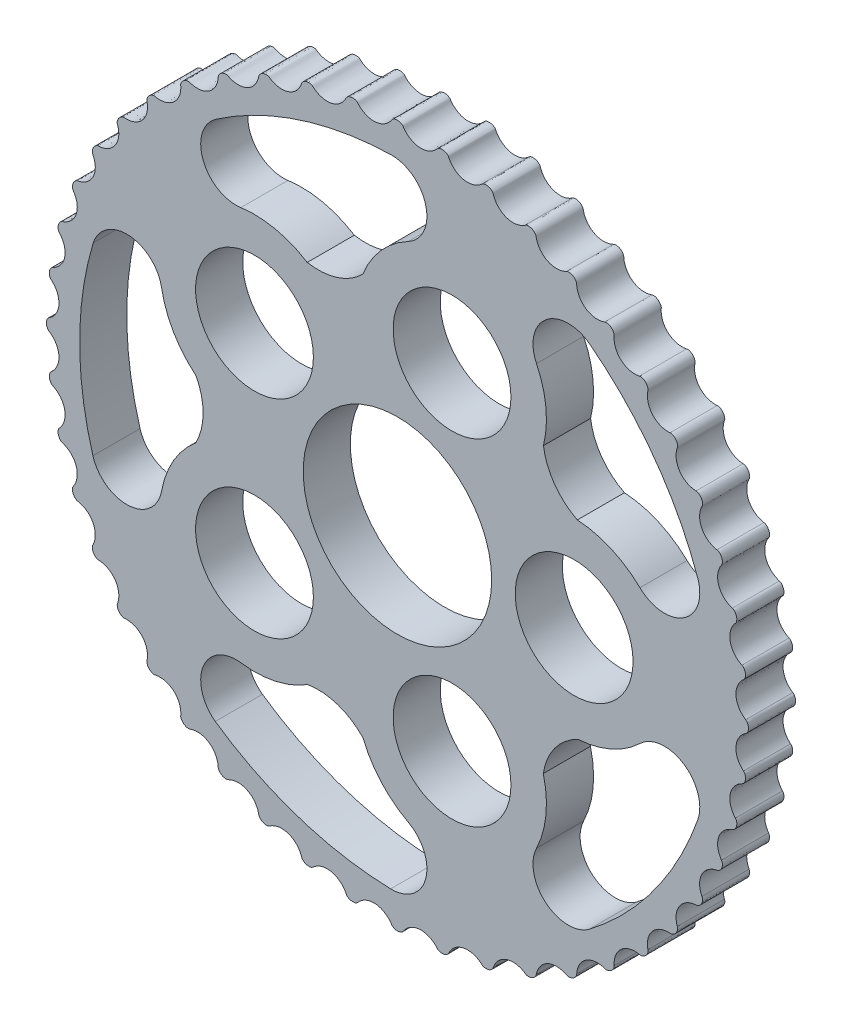
SolidWorks part; units mm, degrees
ref_plane "前视基准面" through (0, 0, 0) normal (0, 0, 1) x (1, 0, 0)
ref_plane "上视基准面" through (0, 0, 0) normal (0, 1, 0) x (1, 0, 0)
ref_plane "右视基准面" through (0, 0, 0) normal (1, 0, 0) x (0, 0, -1)
other "图形1"
other "图形 (闭合) -1"
sketch "草图1" plane through (0, 0, 0) normal (0, 0, 1) x (1, 0, 0)
  circle A14 centre (0, 0) radius 8
  circle A15 centre (-12.1353, 8.8168) radius 5
  circle A16 centre (4.6353, 14.2658) radius 5
  circle A17 centre (15, 0) radius 5
  circle A18 centre (4.6353, -14.2658) radius 5
  circle A19 centre (-12.1353, -8.8168) radius 5
  arc A22 (-15.3994, 22.1779) -> (-0.4976, 26.9948) centre (0.1503, -0.4678) cw
  arc A23 (-15.3994, 22.1779) -> (-13.2927, 16.7327) centre (-13.7012, 19.7047) ccw
  arc A24 (-0.4976, 26.9948) -> (0.9158, 21.3487) centre (-0.4976, 23.9948) cw
  arc A25 (-13.2927, 16.7327) -> (-7.6572, 15.521) centre (-12.143, 8.369) cw
  arc A26 (0.9158, 21.3487) -> (-2.9414, 17.0153) centre (4.8704, 13.9452) ccw
  arc A27 (-7.6572, 15.521) -> (-2.9414, 17.0153) centre (-6.7149, 20.7352) ccw
  arc A28 (12.3951, 12.0786) -> (15.2736, 8.0555) centre (17.6454, 12.7938) ccw
  arc A29 (20.5868, 5.7261) -> (15.2736, 8.0555) centre (14.7677, -0.3227) ccw
  arc A30 (11.8061, 17.8128) -> (12.3951, 12.0786) centre (4.207, 14.1348) cw
  arc A31 (16.3337, 21.499) -> (11.8061, 17.8128) centre (14.5064, 19.1197) ccw
  arc A32 (16.3337, 21.499) -> (25.5198, 8.8152) centre (-0.3985, -0.2875) cw
  arc A33 (25.5198, 8.8152) -> (20.5868, 5.7261) centre (22.6667, 7.8881) cw
  arc A34 (15.3178, -8.0559) -> (12.381, -12.0367) centre (17.6203, -12.8283) ccw
  arc A35 (11.8075, -17.8097) -> (12.381, -12.0367) centre (4.2565, -14.1446) ccw
  arc A36 (20.5892, -5.7238) -> (15.3178, -8.0559) centre (14.743, 0.3668) cw
  arc A37 (25.4942, -8.8907) -> (20.5892, -5.7238) centre (22.6667, -7.8881) ccw
  arc A38 (25.4942, -8.8907) -> (16.2698, -21.5468) centre (-0.3966, 0.2902) cw
  arc A39 (16.2698, -21.5468) -> (11.8075, -17.8097) centre (14.5064, -19.1197) cw
  arc A40 (-2.9282, -17.0575) -> (-7.6217, -15.4946) centre (-6.7554, -20.7221) ccw
  arc A41 (-13.2893, -16.7332) -> (-7.6217, -15.4946) centre (-12.137, -8.4192) ccw
  arc A42 (0.9188, -21.3503) -> (-2.9282, -17.0575) centre (4.9047, -13.9081) cw
  arc A43 (-0.5775, -26.9938) -> (0.9188, -21.3503) centre (-0.4977, -23.9948) ccw
  arc A44 (-0.5775, -26.9938) -> (-15.4646, -22.1318) centre (0.1534, 0.4668) cw
  arc A45 (-15.4646, -22.1318) -> (-13.2893, -16.7332) centre (-13.7012, -19.7047) cw
  arc A46 (-17.1275, -2.4862) -> (-17.0915, 2.4605) centre (-21.7954, 0.0213) ccw
  arc A47 (-20.0208, 7.4681) -> (-17.0915, 2.4605) centre (-11.7576, 8.9413) ccw
  arc A48 (-20.0214, -7.4714) -> (-17.1275, -2.4862) centre (-11.7117, -8.9625) cw
  arc A49 (-25.8511, -7.7923) -> (-20.0214, -7.4714) centre (-22.9742, -6.9415) ccw
  arc A50 (-25.8511, -7.7923) -> (-25.8274, 7.8686) centre (0.4914, -0.0017) cw
  arc A51 (-25.8274, 7.8686) -> (-20.0208, 7.4681) centre (-22.9742, 6.9415) cw
  spline S0 degree 3 poles (-23.7568, 17.5894) (-23.7638, 17.6206) (-23.7873, 17.6724) (-23.7946, 17.7527) (-23.7831, 17.8328) (-23.7576, 17.926) (-23.7125, 18.0342) (-23.6398, 18.1534) (-23.536, 18.2576) (-23.4214, 18.3351) (-23.3276, 18.3772) (-23.2577, 18.3994) (-23.1885, 18.3963) (-23.122, 18.3956) (-23.0375, 18.3863) (-22.9358, 18.3866) (-22.7821, 18.3963) (-22.5426, 18.4408) (-22.2285, 18.5461) (-21.9362, 18.7184) (-21.7337, 18.8947) (-21.622, 19.0229) (-21.5377, 19.1337) (-21.4287, 19.302) (-21.3257, 19.519) (-21.2567, 19.7619) (-21.228, 19.9486) (-21.2184, 20.1013) (-21.2209, 20.2334) (-21.2306, 20.3759) (-21.245, 20.478) (-21.2577, 20.5398) knots 0 0 0 0 0.021407 0.037439 0.053081 0.075244 0.101831 0.131128 0.167942 0.199083 0.222894 0.236703 0.24736 0.268789 0.281242 0.304031 0.336576 0.384054 0.466277 0.556571 0.608579 0.644913 0.669953 0.701577 0.778695 0.829212 0.869703 0.904632 0.931224 0.957906 1 1 1 1
  spline S1 degree 3 poles (-21.2577, 20.5398) (-21.2606, 20.5717) (-21.2771, 20.626) (-21.2739, 20.7066) (-21.252, 20.7845) (-21.2145, 20.8736) (-21.1557, 20.975) (-21.0681, 21.0837) (-20.9516, 21.1735) (-20.8279, 21.2353) (-20.7293, 21.2649) (-20.6571, 21.2777) (-20.5889, 21.2657) (-20.5231, 21.2562) (-20.4405, 21.236) (-20.3397, 21.223) (-20.1859, 21.2126) (-19.9427, 21.2254) (-19.6176, 21.2888) (-19.3053, 21.4215) (-19.0816, 21.5698) (-18.954, 21.6823) (-18.8559, 21.7813) (-18.7259, 21.9339) (-18.5955, 22.1356) (-18.4954, 22.3674) (-18.4426, 22.5488) (-18.4132, 22.6988) (-18.3984, 22.8302) (-18.3893, 22.9727) (-18.3903, 23.0758) (-18.3949, 23.1387) knots 0 0 0 0 0.021407 0.037439 0.05308 0.075244 0.101831 0.131128 0.167942 0.199083 0.222894 0.236703 0.24736 0.268789 0.281242 0.304031 0.336576 0.384054 0.466277 0.556571 0.608579 0.644913 0.669953 0.701577 0.778695 0.829212 0.869703 0.904632 0.931224 0.957906 1 1 1 1
  spline S2 degree 3 poles (-18.3949, 23.1387) (-18.3935, 23.1707) (-18.4028, 23.2268) (-18.3891, 23.3063) (-18.3572, 23.3806) (-18.3085, 23.4641) (-18.2369, 23.5569) (-18.1358, 23.6533) (-18.0086, 23.7271) (-17.8779, 23.7722) (-17.7763, 23.7887) (-17.7031, 23.792) (-17.6371, 23.7711) (-17.573, 23.7532) (-17.4938, 23.7224) (-17.3955, 23.6963) (-17.2445, 23.6659) (-17.0016, 23.6469) (-16.671, 23.6673) (-16.3441, 23.7581) (-16.1029, 23.8759) (-15.9618, 23.9709) (-15.8516, 24.0561) (-15.7028, 24.1905) (-15.5471, 24.3734) (-15.4177, 24.5902) (-15.3416, 24.7631) (-15.2929, 24.9081) (-15.261, 25.0363) (-15.2335, 25.1765) (-15.221, 25.2788) (-15.2173, 25.3418) knots 0 0 0 0 0.021407 0.037439 0.05308 0.075244 0.101831 0.131128 0.167942 0.199083 0.222894 0.236703 0.24736 0.268789 0.281242 0.304031 0.336576 0.384054 0.466277 0.556571 0.608579 0.644913 0.669953 0.701577 0.778695 0.829212 0.869703 0.904632 0.931224 0.957906 1 1 1 1
  spline S3 degree 3 poles (-15.2173, 25.3418) (-15.2118, 25.3733) (-15.2137, 25.4302) (-15.1897, 25.5071) (-15.1484, 25.5767) (-15.0892, 25.6531) (-15.0061, 25.7358) (-14.8933, 25.8181) (-14.7575, 25.8747) (-14.6221, 25.9024) (-14.5192, 25.9054) (-14.4462, 25.8992) (-14.3834, 25.8699) (-14.3222, 25.8437) (-14.2477, 25.8028) (-14.1537, 25.7642) (-14.0079, 25.7143) (-13.7696, 25.6638) (-13.4392, 25.6408) (-13.1032, 25.6882) (-12.8487, 25.7735) (-12.6964, 25.8492) (-12.576, 25.9194) (-12.4109, 26.0331) (-12.2327, 26.1942) (-12.0761, 26.3922) (-11.9781, 26.5537) (-11.9109, 26.6911) (-11.8626, 26.8141) (-11.817, 26.9495) (-11.7912, 27.0493) (-11.7793, 27.1113) knots 0 0 0 0 0.021407 0.037439 0.05308 0.075244 0.101831 0.131128 0.167942 0.199083 0.222894 0.236703 0.24736 0.268789 0.281242 0.304031 0.336576 0.384054 0.466277 0.556571 0.608579 0.644913 0.669953 0.701577 0.778695 0.829212 0.869703 0.904632 0.931224 0.957906 1 1 1 1
  spline S4 degree 3 poles (-11.7793, 27.1113) (-11.7698, 27.1418) (-11.7642, 27.1984) (-11.7304, 27.2716) (-11.6804, 27.3352) (-11.6117, 27.4032) (-11.5185, 27.4743) (-11.3959, 27.5412) (-11.254, 27.5795) (-11.116, 27.5894) (-11.0137, 27.579) (-10.9421, 27.5632) (-10.8837, 27.526) (-10.8264, 27.492) (-10.7579, 27.4418) (-10.6697, 27.3912) (-10.5317, 27.3227) (-10.3021, 27.2415) (-9.9774, 27.1756) (-9.6381, 27.1787) (-9.3746, 27.2301) (-9.2138, 27.2853) (-9.0853, 27.3391) (-8.9068, 27.4304) (-8.7091, 27.5668) (-8.5279, 27.7427) (-8.4097, 27.89) (-8.3251, 28.0174) (-8.2612, 28.1331) (-8.1983, 28.2613) (-8.1597, 28.357) (-8.1398, 28.4168) knots 0 0 0 0 0.021407 0.037439 0.05308 0.075244 0.101831 0.131128 0.167942 0.199083 0.222894 0.236703 0.24736 0.268789 0.281242 0.304031 0.336576 0.384054 0.466277 0.556571 0.608579 0.644913 0.669953 0.701577 0.778695 0.829212 0.869703 0.904632 0.931224 0.957906 1 1 1 1
  spline S5 degree 3 poles (-8.1398, 28.4168) (-8.1264, 28.4459) (-8.1135, 28.5012) (-8.0704, 28.5694) (-8.0125, 28.6259) (-7.9355, 28.6844) (-7.8339, 28.7427) (-7.7036, 28.7931) (-7.5578, 28.8125) (-7.4198, 28.8043) (-7.3197, 28.7806) (-7.2507, 28.7556) (-7.1977, 28.7111) (-7.1454, 28.67) (-7.084, 28.6112) (-7.0032, 28.5495) (-6.8752, 28.4636) (-6.6582, 28.3531) (-6.3449, 28.2455) (-6.0081, 28.2042) (-5.7402, 28.2208) (-5.5735, 28.2545) (-5.4391, 28.2911) (-5.2502, 28.3583) (-5.0364, 28.4677) (-4.8338, 28.6184) (-4.6974, 28.7491) (-4.5969, 28.8644) (-4.5184, 28.9707) (-4.4393, 29.0897) (-4.3885, 29.1794) (-4.3611, 29.2362) knots 0 0 0 0 0.021407 0.037439 0.05308 0.075244 0.101831 0.131128 0.167942 0.199083 0.222894 0.236703 0.24736 0.268789 0.281242 0.304031 0.336576 0.384054 0.466277 0.556571 0.608579 0.644913 0.669953 0.701577 0.778695 0.829212 0.869703 0.904632 0.931224 0.957906 1 1 1 1
  spline S6 degree 3 poles (-4.3611, 29.2362) (-4.3439, 29.2632) (-4.3239, 29.3164) (-4.2723, 29.3784) (-4.2075, 29.4268) (-4.1236, 29.4748) (-4.0152, 29.5193) (-3.8794, 29.5523) (-3.7324, 29.5525) (-3.5966, 29.5263) (-3.5004, 29.4898) (-3.4353, 29.456) (-3.3886, 29.4049) (-3.3421, 29.3573) (-3.2889, 29.2911) (-3.2168, 29.2194) (-3.1012, 29.1175) (-2.9004, 28.9796) (-2.6038, 28.832) (-2.2753, 28.7471) (-2.0075, 28.7286) (-1.8379, 28.7402) (-1.6998, 28.759) (-1.5038, 28.8009) (-1.2775, 28.8815) (-1.057, 29.0045) (-0.9047, 29.1163) (-0.79, 29.2174) (-0.6983, 29.3126) (-0.6043, 29.4202) (-0.5423, 29.5026) (-0.5077, 29.5553) knots 0 0 0 0 0.021407 0.037439 0.05308 0.075244 0.101831 0.131128 0.167942 0.199083 0.222894 0.236703 0.24736 0.268789 0.281242 0.304031 0.336576 0.384054 0.466277 0.556571 0.608579 0.644913 0.669953 0.701577 0.778695 0.829212 0.869703 0.904632 0.931224 0.957906 1 1 1 1
  spline S7 degree 3 poles (-0.5077, 29.5553) (-0.4871, 29.5799) (-0.4604, 29.63) (-0.4011, 29.6847) (-0.3305, 29.7243) (-0.2411, 29.7608) (-0.1278, 29.7909) (0.0111, 29.8058) (0.1569, 29.7869) (0.2881, 29.7432) (0.3787, 29.6944) (0.4388, 29.6524) (0.4785, 29.5957) (0.5184, 29.5424) (0.5625, 29.4698) (0.6246, 29.3893) (0.726, 29.2732) (0.907, 29.1103) (1.1818, 28.9252) (1.4964, 28.7982) (1.7595, 28.7449) (1.9292, 28.7343) (2.0685, 28.7349) (2.2684, 28.7508) (2.5032, 28.8012) (2.7379, 28.8944) (2.9035, 28.9853) (3.0304, 29.0706) (3.1338, 29.153) (3.2409, 29.2474) (3.3132, 29.321) (3.3544, 29.3687) knots 0 0 0 0 0.021407 0.037439 0.05308 0.075244 0.101831 0.131128 0.167942 0.199083 0.222894 0.236703 0.24736 0.268789 0.281242 0.304031 0.336576 0.384054 0.466277 0.556571 0.608579 0.644913 0.669953 0.701577 0.778695 0.829212 0.869703 0.904632 0.931224 0.957906 1 1 1 1
  spline S8 degree 3 poles (3.3544, 29.3687) (3.378, 29.3904) (3.4111, 29.4366) (3.477, 29.4831) (3.5521, 29.5131) (3.6456, 29.5377) (3.7618, 29.5527) (3.9014, 29.5494) (4.0435, 29.5116) (4.1679, 29.4511) (4.2514, 29.3909) (4.3055, 29.3415) (4.3374, 29.28) (4.37, 29.222) (4.4043, 29.1442) (4.4553, 29.0563) (4.5407, 28.928) (4.6989, 28.7429) (4.9471, 28.5235) (5.2425, 28.3565) (5.4964, 28.2693) (5.6633, 28.2366) (5.8015, 28.219) (6.0017, 28.2088) (6.2411, 28.2281) (6.4859, 28.2898) (6.662, 28.3583) (6.799, 28.4263) (6.9122, 28.4945) (7.0308, 28.5742) (7.112, 28.6377) (7.1591, 28.6796) knots 0 0 0 0 0.021407 0.037439 0.05308 0.075244 0.101831 0.131128 0.167942 0.199083 0.222894 0.236703 0.24736 0.268789 0.281242 0.304031 0.336576 0.384054 0.466277 0.556571 0.608579 0.644913 0.669953 0.701577 0.778695 0.829212 0.869703 0.904632 0.931224 0.957906 1 1 1 1
  spline S9 degree 3 poles (7.1591, 28.6796) (7.1853, 28.698) (7.2241, 28.7395) (7.2955, 28.777) (7.3739, 28.797) (7.4698, 28.8092) (7.587, 28.8088) (7.725, 28.7873) (7.861, 28.7313) (7.9764, 28.6551) (8.0513, 28.5845) (8.0985, 28.5285) (8.1221, 28.4634) (8.1469, 28.4016) (8.1707, 28.32) (8.2098, 28.2262) (8.2777, 28.0878) (8.4104, 27.8836) (8.6279, 27.6337) (8.8989, 27.4296) (9.1392, 27.31) (9.3004, 27.2558) (9.4352, 27.2204) (9.6323, 27.1841) (9.8722, 27.1719) (10.123, 27.2012) (10.3065, 27.2461) (10.4512, 27.2957) (10.5723, 27.3485) (10.7003, 27.412) (10.7891, 27.4644) (10.8413, 27.4998) knots 0 0 0 0 0.021407 0.037439 0.05308 0.075244 0.101831 0.131128 0.167942 0.199083 0.222894 0.236703 0.24736 0.268789 0.281242 0.304031 0.336576 0.384054 0.466277 0.556571 0.608579 0.644913 0.669953 0.701577 0.778695 0.829212 0.869703 0.904632 0.931224 0.957906 1 1 1 1
  spline S10 degree 3 poles (10.8413, 27.4998) (10.8697, 27.5146) (10.9136, 27.5507) (10.9893, 27.5786) (11.0696, 27.5881) (11.1663, 27.5877) (11.2824, 27.5721) (11.4164, 27.5327) (11.5439, 27.4594) (11.6484, 27.3688) (11.7134, 27.2891) (11.7529, 27.2273) (11.7679, 27.1597) (11.7843, 27.0952) (11.7973, 27.0113) (11.8239, 26.9131) (11.8731, 26.7671) (11.978, 26.5473) (12.161, 26.2712) (12.4031, 26.0334) (12.6257, 25.8835) (12.7785, 25.8087) (12.9074, 25.756) (13.0982, 25.6942) (13.3344, 25.6509) (13.5869, 25.6472) (13.7747, 25.6678) (13.9246, 25.698) (14.0516, 25.7346) (14.1867, 25.7808) (14.2816, 25.8212) (14.338, 25.8495) knots 0 0 0 0 0.021407 0.037439 0.05308 0.075244 0.101831 0.131128 0.167942 0.199083 0.222894 0.236703 0.24736 0.268789 0.281242 0.304031 0.336576 0.384054 0.466277 0.556571 0.608579 0.644913 0.669953 0.701577 0.778695 0.829212 0.869703 0.904632 0.931224 0.957906 1 1 1 1
  spline S11 degree 3 poles (14.338, 25.8495) (14.3681, 25.8605) (14.4163, 25.8905) (14.495, 25.9082) (14.5759, 25.9072) (14.6717, 25.8942) (14.7848, 25.8635) (14.9125, 25.8071) (15.0293, 25.7177) (15.1211, 25.6143) (15.1752, 25.5267) (15.2063, 25.4603) (15.2122, 25.3913) (15.2202, 25.3253) (15.222, 25.2403) (15.2356, 25.1396) (15.2653, 24.9884) (15.3406, 24.7567) (15.486, 24.4591) (15.695, 24.1918) (15.8962, 24.0141) (16.0379, 23.92) (16.1588, 23.8508) (16.3399, 23.7648) (16.5685, 23.691) (16.8183, 23.6543) (17.0071, 23.6502) (17.1597, 23.6607) (17.2904, 23.6803) (17.4305, 23.7085) (17.5298, 23.7361) (17.5894, 23.7568) knots 0 0 0 0 0.021407 0.037439 0.05308 0.075244 0.101831 0.131128 0.167942 0.199083 0.222894 0.236703 0.24736 0.268789 0.281242 0.304031 0.336576 0.384054 0.466277 0.556571 0.608579 0.644913 0.669953 0.701577 0.778695 0.829212 0.869703 0.904632 0.931224 0.957906 1 1 1 1
  spline S12 degree 3 poles (17.5894, 23.7568) (17.6206, 23.7638) (17.6724, 23.7873) (17.7527, 23.7946) (17.8328, 23.7831) (17.926, 23.7576) (18.0342, 23.7125) (18.1534, 23.6398) (18.2576, 23.536) (18.3351, 23.4214) (18.3772, 23.3276) (18.3994, 23.2577) (18.3963, 23.1885) (18.3956, 23.122) (18.3863, 23.0375) (18.3866, 22.9358) (18.3963, 22.7821) (18.4408, 22.5426) (18.5461, 22.2285) (18.7184, 21.9362) (18.8947, 21.7337) (19.0229, 21.622) (19.1337, 21.5377) (19.302, 21.4287) (19.519, 21.3257) (19.7619, 21.2567) (19.9486, 21.228) (20.1013, 21.2184) (20.2334, 21.2209) (20.3759, 21.2306) (20.478, 21.245) (20.5398, 21.2577) knots 0 0 0 0 0.021407 0.037439 0.05308 0.075244 0.101831 0.131128 0.167942 0.199083 0.222894 0.236703 0.24736 0.268789 0.281242 0.304031 0.336576 0.384054 0.466277 0.556571 0.608579 0.644913 0.669953 0.701577 0.778695 0.829212 0.869703 0.904632 0.931224 0.957906 1 1 1 1
  spline S13 degree 3 poles (20.5398, 21.2577) (20.5717, 21.2606) (20.626, 21.2771) (20.7066, 21.2739) (20.7845, 21.252) (20.8736, 21.2145) (20.975, 21.1557) (21.0837, 21.0681) (21.1735, 20.9516) (21.2353, 20.8279) (21.2649, 20.7293) (21.2777, 20.6571) (21.2657, 20.5889) (21.2562, 20.5231) (21.236, 20.4405) (21.223, 20.3397) (21.2126, 20.1859) (21.2254, 19.9427) (21.2888, 19.6176) (21.4215, 19.3053) (21.5698, 19.0816) (21.6823, 18.954) (21.7813, 18.8559) (21.9339, 18.7259) (22.1356, 18.5955) (22.3674, 18.4954) (22.5488, 18.4426) (22.6988, 18.4132) (22.8302, 18.3984) (22.9727, 18.3893) (23.0758, 18.3903) (23.1387, 18.3949) knots 0 0 0 0 0.021407 0.037439 0.05308 0.075244 0.101831 0.131128 0.167942 0.199083 0.222894 0.236703 0.24736 0.268789 0.281242 0.304031 0.336576 0.384054 0.466277 0.556571 0.608579 0.644913 0.669953 0.701577 0.778695 0.829212 0.869703 0.904632 0.931224 0.957906 1 1 1 1
  spline S14 degree 3 poles (23.1387, 18.3949) (23.1707, 18.3935) (23.2268, 18.4028) (23.3063, 18.3891) (23.3806, 18.3572) (23.4641, 18.3085) (23.5569, 18.2369) (23.6533, 18.1358) (23.7271, 18.0086) (23.7722, 17.8779) (23.7887, 17.7763) (23.792, 17.7031) (23.7711, 17.6371) (23.7532, 17.573) (23.7224, 17.4938) (23.6963, 17.3955) (23.6659, 17.2445) (23.6469, 17.0016) (23.6673, 16.671) (23.7581, 16.3441) (23.8759, 16.1029) (23.9709, 15.9618) (24.0561, 15.8516) (24.1905, 15.7028) (24.3734, 15.5471) (24.5902, 15.4177) (24.7631, 15.3416) (24.9081, 15.2929) (25.0363, 15.261) (25.1765, 15.2335) (25.2788, 15.221) (25.3418, 15.2173) knots 0 0 0 0 0.021407 0.037439 0.05308 0.075244 0.101831 0.131128 0.167942 0.199083 0.222894 0.236703 0.24736 0.268789 0.281242 0.304031 0.336576 0.384054 0.466277 0.556571 0.608579 0.644913 0.669953 0.701577 0.778695 0.829212 0.869703 0.904632 0.931224 0.957906 1 1 1 1
  spline S15 degree 3 poles (25.3418, 15.2173) (25.3733, 15.2118) (25.4302, 15.2137) (25.5071, 15.1897) (25.5767, 15.1484) (25.6531, 15.0892) (25.7358, 15.0061) (25.8181, 14.8933) (25.8747, 14.7575) (25.9024, 14.6221) (25.9054, 14.5192) (25.8992, 14.4462) (25.8699, 14.3834) (25.8437, 14.3222) (25.8028, 14.2477) (25.7642, 14.1537) (25.7143, 14.0079) (25.6638, 13.7696) (25.6408, 13.4392) (25.6882, 13.1032) (25.7735, 12.8487) (25.8492, 12.6964) (25.9194, 12.576) (26.0331, 12.4109) (26.1942, 12.2327) (26.3922, 12.0761) (26.5537, 11.9781) (26.6911, 11.9109) (26.8141, 11.8626) (26.9495, 11.817) (27.0493, 11.7912) (27.1113, 11.7793) knots 0 0 0 0 0.021407 0.037439 0.05308 0.075244 0.101831 0.131128 0.167942 0.199083 0.222894 0.236703 0.24736 0.268789 0.281242 0.304031 0.336576 0.384054 0.466277 0.556571 0.608579 0.644913 0.669953 0.701577 0.778695 0.829212 0.869703 0.904632 0.931224 0.957906 1 1 1 1
  spline S16 degree 3 poles (27.1113, 11.7793) (27.1418, 11.7698) (27.1984, 11.7642) (27.2716, 11.7304) (27.3352, 11.6804) (27.4032, 11.6117) (27.4743, 11.5185) (27.5412, 11.3959) (27.5795, 11.254) (27.5894, 11.116) (27.579, 11.0137) (27.5632, 10.9421) (27.526, 10.8837) (27.492, 10.8264) (27.4418, 10.7579) (27.3912, 10.6697) (27.3227, 10.5317) (27.2415, 10.3021) (27.1756, 9.9774) (27.1787, 9.6381) (27.2301, 9.3746) (27.2853, 9.2138) (27.3391, 9.0853) (27.4304, 8.9068) (27.5668, 8.7091) (27.7427, 8.5279) (27.89, 8.4097) (28.0174, 8.3251) (28.1331, 8.2612) (28.2613, 8.1983) (28.357, 8.1597) (28.4168, 8.1398) knots 0 0 0 0 0.021407 0.037439 0.05308 0.075244 0.101831 0.131128 0.167942 0.199083 0.222894 0.236703 0.24736 0.268789 0.281242 0.304031 0.336576 0.384054 0.466277 0.556571 0.608579 0.644913 0.669953 0.701577 0.778695 0.829212 0.869703 0.904632 0.931224 0.957906 1 1 1 1
  spline S17 degree 3 poles (28.4168, 8.1398) (28.4459, 8.1264) (28.5012, 8.1135) (28.5694, 8.0704) (28.6259, 8.0125) (28.6844, 7.9355) (28.7427, 7.8339) (28.7931, 7.7036) (28.8125, 7.5578) (28.8043, 7.4198) (28.7806, 7.3197) (28.7556, 7.2507) (28.7111, 7.1977) (28.67, 7.1454) (28.6112, 7.084) (28.5495, 7.0032) (28.4636, 6.8752) (28.3531, 6.6582) (28.2455, 6.3449) (28.2042, 6.0081) (28.2208, 5.7402) (28.2545, 5.5735) (28.2911, 5.4391) (28.3583, 5.2502) (28.4677, 5.0364) (28.6184, 4.8338) (28.7491, 4.6974) (28.8644, 4.5969) (28.9707, 4.5184) (29.0897, 4.4393) (29.1794, 4.3885) (29.2362, 4.3611) knots 0 0 0 0 0.021407 0.037439 0.05308 0.075244 0.101831 0.131128 0.167942 0.199083 0.222894 0.236703 0.24736 0.268789 0.281242 0.304031 0.336576 0.384054 0.466277 0.556571 0.608579 0.644913 0.669953 0.701577 0.778695 0.829212 0.869703 0.904632 0.931224 0.957906 1 1 1 1
  spline S18 degree 3 poles (29.2362, 4.3611) (29.2632, 4.3439) (29.3164, 4.3239) (29.3784, 4.2723) (29.4268, 4.2075) (29.4748, 4.1236) (29.5193, 4.0152) (29.5523, 3.8794) (29.5525, 3.7324) (29.5263, 3.5966) (29.4898, 3.5004) (29.456, 3.4353) (29.4049, 3.3886) (29.3573, 3.3421) (29.2911, 3.2889) (29.2194, 3.2168) (29.1175, 3.1012) (28.9796, 2.9004) (28.832, 2.6038) (28.7471, 2.2753) (28.7286, 2.0075) (28.7402, 1.8379) (28.759, 1.6998) (28.8009, 1.5038) (28.8815, 1.2775) (29.0045, 1.057) (29.1163, 0.9047) (29.2174, 0.79) (29.3126, 0.6983) (29.4202, 0.6043) (29.5026, 0.5423) (29.5553, 0.5077) knots 0 0 0 0 0.021407 0.037439 0.05308 0.075244 0.101831 0.131128 0.167942 0.199083 0.222894 0.236703 0.24736 0.268789 0.281242 0.304031 0.336576 0.384054 0.466277 0.556571 0.608579 0.644913 0.669953 0.701577 0.778695 0.829212 0.869703 0.904632 0.931224 0.957906 1 1 1 1
  spline S19 degree 3 poles (29.5553, 0.5077) (29.5799, 0.4871) (29.63, 0.4604) (29.6847, 0.4011) (29.7243, 0.3305) (29.7608, 0.2411) (29.7909, 0.1278) (29.8058, -0.0111) (29.7869, -0.1569) (29.7432, -0.2881) (29.6944, -0.3787) (29.6524, -0.4388) (29.5957, -0.4785) (29.5424, -0.5184) (29.4698, -0.5625) (29.3893, -0.6246) (29.2732, -0.726) (29.1103, -0.907) (28.9252, -1.1818) (28.7982, -1.4964) (28.7449, -1.7595) (28.7343, -1.9292) (28.7349, -2.0685) (28.7508, -2.2684) (28.8012, -2.5032) (28.8944, -2.7379) (28.9853, -2.9035) (29.0706, -3.0304) (29.153, -3.1338) (29.2474, -3.2409) (29.321, -3.3132) (29.3687, -3.3544) knots 0 0 0 0 0.021407 0.037439 0.05308 0.075244 0.101831 0.131128 0.167942 0.199083 0.222894 0.236703 0.24736 0.268789 0.281242 0.304031 0.336576 0.384054 0.466277 0.556571 0.608579 0.644913 0.669953 0.701577 0.778695 0.829212 0.869703 0.904632 0.931224 0.957906 1 1 1 1
  spline S20 degree 3 poles (29.3687, -3.3544) (29.3904, -3.378) (29.4366, -3.4111) (29.4831, -3.477) (29.5131, -3.5521) (29.5377, -3.6456) (29.5527, -3.7618) (29.5494, -3.9014) (29.5116, -4.0435) (29.4511, -4.1679) (29.3909, -4.2514) (29.3415, -4.3055) (29.28, -4.3374) (29.222, -4.37) (29.1442, -4.4043) (29.0563, -4.4553) (28.928, -4.5407) (28.7429, -4.6989) (28.5235, -4.9471) (28.3565, -5.2425) (28.2693, -5.4964) (28.2366, -5.6633) (28.219, -5.8015) (28.2088, -6.0017) (28.2281, -6.2411) (28.2898, -6.4859) (28.3583, -6.662) (28.4263, -6.799) (28.4945, -6.9122) (28.5742, -7.0308) (28.6377, -7.112) (28.6796, -7.1591) knots 0 0 0 0 0.021407 0.037439 0.05308 0.075244 0.101831 0.131128 0.167942 0.199083 0.222894 0.236703 0.24736 0.268789 0.281242 0.304031 0.336576 0.384054 0.466277 0.556571 0.608579 0.644913 0.669953 0.701577 0.778695 0.829212 0.869703 0.904632 0.931224 0.957906 1 1 1 1
  spline S21 degree 3 poles (28.6796, -7.1591) (28.698, -7.1853) (28.7395, -7.2241) (28.777, -7.2955) (28.797, -7.3739) (28.8092, -7.4698) (28.8088, -7.587) (28.7873, -7.725) (28.7313, -7.861) (28.6551, -7.9764) (28.5845, -8.0513) (28.5285, -8.0985) (28.4634, -8.1221) (28.4016, -8.1469) (28.32, -8.1707) (28.2262, -8.2098) (28.0878, -8.2777) (27.8836, -8.4104) (27.6337, -8.6279) (27.4296, -8.8989) (27.31, -9.1392) (27.2558, -9.3004) (27.2204, -9.4352) (27.1841, -9.6323) (27.1719, -9.8722) (27.2012, -10.123) (27.2461, -10.3065) (27.2957, -10.4512) (27.3485, -10.5723) (27.412, -10.7003) (27.4644, -10.7891) (27.4998, -10.8413) knots 0 0 0 0 0.021407 0.037439 0.05308 0.075244 0.101831 0.131128 0.167942 0.199083 0.222894 0.236703 0.24736 0.268789 0.281242 0.304031 0.336576 0.384054 0.466277 0.556571 0.608579 0.644913 0.669953 0.701577 0.778695 0.829212 0.869703 0.904632 0.931224 0.957906 1 1 1 1
  spline S22 degree 3 poles (27.4998, -10.8413) (27.5146, -10.8697) (27.5507, -10.9136) (27.5786, -10.9893) (27.5881, -11.0696) (27.5877, -11.1663) (27.5721, -11.2824) (27.5327, -11.4164) (27.4594, -11.5439) (27.3688, -11.6484) (27.2891, -11.7134) (27.2273, -11.7529) (27.1597, -11.7679) (27.0952, -11.7843) (27.0113, -11.7973) (26.9131, -11.8239) (26.7671, -11.8731) (26.5473, -11.978) (26.2712, -12.161) (26.0334, -12.4031) (25.8835, -12.6257) (25.8087, -12.7785) (25.756, -12.9074) (25.6942, -13.0982) (25.6509, -13.3344) (25.6472, -13.5869) (25.6678, -13.7747) (25.698, -13.9246) (25.7346, -14.0516) (25.7808, -14.1867) (25.8212, -14.2816) (25.8495, -14.338) knots 0 0 0 0 0.021407 0.037439 0.05308 0.075244 0.101831 0.131128 0.167942 0.199083 0.222894 0.236703 0.24736 0.268789 0.281242 0.304031 0.336576 0.384054 0.466277 0.556571 0.608579 0.644913 0.669953 0.701577 0.778695 0.829212 0.869703 0.904632 0.931224 0.957906 1 1 1 1
  spline S23 degree 3 poles (25.8495, -14.338) (25.8605, -14.3681) (25.8905, -14.4163) (25.9082, -14.495) (25.9072, -14.5759) (25.8942, -14.6717) (25.8635, -14.7848) (25.8071, -14.9125) (25.7177, -15.0293) (25.6143, -15.1211) (25.5267, -15.1752) (25.4603, -15.2063) (25.3913, -15.2122) (25.3253, -15.2202) (25.2403, -15.222) (25.1396, -15.2356) (24.9884, -15.2653) (24.7567, -15.3406) (24.4591, -15.486) (24.1918, -15.695) (24.0141, -15.8962) (23.92, -16.0379) (23.8508, -16.1588) (23.7648, -16.3399) (23.691, -16.5685) (23.6543, -16.8183) (23.6502, -17.0071) (23.6607, -17.1597) (23.6803, -17.2904) (23.7085, -17.4305) (23.7361, -17.5298) (23.7568, -17.5894) knots 0 0 0 0 0.021407 0.037439 0.05308 0.075244 0.101831 0.131128 0.167942 0.199083 0.222894 0.236703 0.24736 0.268789 0.281242 0.304031 0.336576 0.384054 0.466277 0.556571 0.608579 0.644913 0.669953 0.701577 0.778695 0.829212 0.869703 0.904632 0.931224 0.957906 1 1 1 1
  spline S24 degree 3 poles (23.7568, -17.5894) (23.7638, -17.6206) (23.7873, -17.6724) (23.7946, -17.7527) (23.7831, -17.8328) (23.7576, -17.926) (23.7125, -18.0342) (23.6398, -18.1534) (23.536, -18.2576) (23.4214, -18.3351) (23.3276, -18.3772) (23.2577, -18.3994) (23.1885, -18.3963) (23.122, -18.3956) (23.0375, -18.3863) (22.9358, -18.3866) (22.7821, -18.3963) (22.5426, -18.4408) (22.2285, -18.5461) (21.9362, -18.7184) (21.7337, -18.8947) (21.622, -19.0229) (21.5377, -19.1337) (21.4287, -19.302) (21.3257, -19.519) (21.2567, -19.7619) (21.228, -19.9486) (21.2184, -20.1013) (21.2209, -20.2334) (21.2306, -20.3759) (21.245, -20.478) (21.2577, -20.5398) knots 0 0 0 0 0.021407 0.037439 0.05308 0.075244 0.101831 0.131128 0.167942 0.199083 0.222894 0.236703 0.24736 0.268789 0.281242 0.304031 0.336576 0.384054 0.466277 0.556571 0.608579 0.644913 0.669953 0.701577 0.778695 0.829212 0.869703 0.904632 0.931224 0.957906 1 1 1 1
  spline S25 degree 3 poles (21.2577, -20.5398) (21.2606, -20.5717) (21.2771, -20.626) (21.2739, -20.7066) (21.252, -20.7845) (21.2145, -20.8736) (21.1557, -20.975) (21.0681, -21.0837) (20.9516, -21.1735) (20.8279, -21.2353) (20.7293, -21.2649) (20.6571, -21.2777) (20.5889, -21.2657) (20.5231, -21.2562) (20.4405, -21.236) (20.3397, -21.223) (20.1859, -21.2126) (19.9427, -21.2254) (19.6176, -21.2888) (19.3053, -21.4215) (19.0816, -21.5698) (18.954, -21.6823) (18.8559, -21.7813) (18.7259, -21.9339) (18.5955, -22.1356) (18.4954, -22.3674) (18.4426, -22.5488) (18.4132, -22.6988) (18.3984, -22.8302) (18.3893, -22.9727) (18.3903, -23.0758) (18.3949, -23.1387) knots 0 0 0 0 0.021407 0.037439 0.05308 0.075244 0.101831 0.131128 0.167942 0.199083 0.222894 0.236703 0.24736 0.268789 0.281242 0.304031 0.336576 0.384054 0.466277 0.556571 0.608579 0.644913 0.669953 0.701577 0.778695 0.829212 0.869703 0.904632 0.931224 0.957906 1 1 1 1
  spline S26 degree 3 poles (18.3949, -23.1387) (18.3935, -23.1707) (18.4028, -23.2268) (18.3891, -23.3063) (18.3572, -23.3806) (18.3085, -23.4641) (18.2369, -23.5569) (18.1358, -23.6533) (18.0086, -23.7271) (17.8779, -23.7722) (17.7763, -23.7887) (17.7031, -23.792) (17.6371, -23.7711) (17.573, -23.7532) (17.4938, -23.7224) (17.3955, -23.6963) (17.2445, -23.6659) (17.0016, -23.6469) (16.671, -23.6673) (16.3441, -23.7581) (16.1029, -23.8759) (15.9618, -23.9709) (15.8516, -24.0561) (15.7028, -24.1905) (15.5471, -24.3734) (15.4177, -24.5902) (15.3416, -24.7631) (15.2929, -24.9081) (15.261, -25.0363) (15.2335, -25.1765) (15.221, -25.2788) (15.2173, -25.3418) knots 0 0 0 0 0.021407 0.037439 0.05308 0.075244 0.101831 0.131128 0.167942 0.199083 0.222894 0.236703 0.24736 0.268789 0.281242 0.304031 0.336576 0.384054 0.466277 0.556571 0.608579 0.644913 0.669953 0.701577 0.778695 0.829212 0.869703 0.904632 0.931224 0.957906 1 1 1 1
  spline S27 degree 3 poles (15.2173, -25.3418) (15.2118, -25.3733) (15.2137, -25.4302) (15.1897, -25.5071) (15.1484, -25.5767) (15.0892, -25.6531) (15.0061, -25.7358) (14.8933, -25.8181) (14.7575, -25.8747) (14.6221, -25.9024) (14.5192, -25.9054) (14.4462, -25.8992) (14.3834, -25.8699) (14.3222, -25.8437) (14.2477, -25.8028) (14.1537, -25.7642) (14.0079, -25.7143) (13.7696, -25.6638) (13.4392, -25.6408) (13.1032, -25.6882) (12.8487, -25.7735) (12.6964, -25.8492) (12.576, -25.9194) (12.4109, -26.0331) (12.2327, -26.1942) (12.0761, -26.3922) (11.9781, -26.5537) (11.9109, -26.6911) (11.8626, -26.8141) (11.817, -26.9495) (11.7912, -27.0493) (11.7793, -27.1113) knots 0 0 0 0 0.021407 0.037439 0.05308 0.075244 0.101831 0.131128 0.167942 0.199083 0.222894 0.236703 0.24736 0.268789 0.281242 0.304031 0.336576 0.384054 0.466277 0.556571 0.608579 0.644913 0.669953 0.701577 0.778695 0.829212 0.869703 0.904632 0.931224 0.957906 1 1 1 1
  spline S28 degree 3 poles (11.7793, -27.1113) (11.7698, -27.1418) (11.7642, -27.1984) (11.7304, -27.2716) (11.6804, -27.3352) (11.6117, -27.4032) (11.5185, -27.4743) (11.3959, -27.5412) (11.254, -27.5795) (11.116, -27.5894) (11.0137, -27.579) (10.9421, -27.5632) (10.8837, -27.526) (10.8264, -27.492) (10.7579, -27.4418) (10.6697, -27.3912) (10.5317, -27.3227) (10.3021, -27.2415) (9.9774, -27.1756) (9.6381, -27.1787) (9.3746, -27.2301) (9.2138, -27.2853) (9.0853, -27.3391) (8.9068, -27.4304) (8.7091, -27.5668) (8.5279, -27.7427) (8.4097, -27.89) (8.3251, -28.0174) (8.2612, -28.1331) (8.1983, -28.2613) (8.1597, -28.357) (8.1398, -28.4168) knots 0 0 0 0 0.021407 0.037439 0.05308 0.075244 0.101831 0.131128 0.167942 0.199083 0.222894 0.236703 0.24736 0.268789 0.281242 0.304031 0.336576 0.384054 0.466277 0.556571 0.608579 0.644913 0.669953 0.701577 0.778695 0.829212 0.869703 0.904632 0.931224 0.957906 1 1 1 1
  spline S29 degree 3 poles (8.1398, -28.4168) (8.1264, -28.4459) (8.1135, -28.5012) (8.0704, -28.5694) (8.0125, -28.6259) (7.9355, -28.6844) (7.8339, -28.7427) (7.7036, -28.7931) (7.5578, -28.8125) (7.4198, -28.8043) (7.3197, -28.7806) (7.2507, -28.7556) (7.1977, -28.7111) (7.1454, -28.67) (7.084, -28.6112) (7.0032, -28.5495) (6.8752, -28.4636) (6.6582, -28.3531) (6.3449, -28.2455) (6.0081, -28.2042) (5.7402, -28.2208) (5.5735, -28.2545) (5.4391, -28.2911) (5.2502, -28.3583) (5.0364, -28.4677) (4.8338, -28.6184) (4.6974, -28.7491) (4.5969, -28.8644) (4.5184, -28.9707) (4.4393, -29.0897) (4.3885, -29.1794) (4.3611, -29.2362) knots 0 0 0 0 0.021407 0.037439 0.05308 0.075244 0.101831 0.131128 0.167942 0.199083 0.222894 0.236703 0.24736 0.268789 0.281242 0.304031 0.336576 0.384054 0.466277 0.556571 0.608579 0.644913 0.669953 0.701577 0.778695 0.829212 0.869703 0.904632 0.931224 0.957906 1 1 1 1
  spline S30 degree 3 poles (4.3611, -29.2362) (4.3439, -29.2632) (4.3239, -29.3164) (4.2723, -29.3784) (4.2075, -29.4268) (4.1236, -29.4748) (4.0152, -29.5193) (3.8794, -29.5523) (3.7324, -29.5525) (3.5966, -29.5263) (3.5004, -29.4898) (3.4353, -29.456) (3.3886, -29.4049) (3.3421, -29.3573) (3.2889, -29.2911) (3.2168, -29.2194) (3.1012, -29.1175) (2.9004, -28.9796) (2.6038, -28.832) (2.2753, -28.7471) (2.0075, -28.7286) (1.8379, -28.7402) (1.6998, -28.759) (1.5038, -28.8009) (1.2775, -28.8815) (1.057, -29.0045) (0.9047, -29.1163) (0.79, -29.2174) (0.6983, -29.3126) (0.6043, -29.4202) (0.5423, -29.5026) (0.5077, -29.5553) knots 0 0 0 0 0.021407 0.037439 0.05308 0.075244 0.101831 0.131128 0.167942 0.199083 0.222894 0.236703 0.24736 0.268789 0.281242 0.304031 0.336576 0.384054 0.466277 0.556571 0.608579 0.644913 0.669953 0.701577 0.778695 0.829212 0.869703 0.904632 0.931224 0.957906 1 1 1 1
  spline S31 degree 3 poles (0.5077, -29.5553) (0.4871, -29.5799) (0.4604, -29.63) (0.4011, -29.6847) (0.3305, -29.7243) (0.2411, -29.7608) (0.1278, -29.7909) (-0.0111, -29.8058) (-0.1569, -29.7869) (-0.2881, -29.7432) (-0.3787, -29.6944) (-0.4388, -29.6524) (-0.4785, -29.5957) (-0.5184, -29.5424) (-0.5625, -29.4698) (-0.6246, -29.3893) (-0.726, -29.2732) (-0.907, -29.1103) (-1.1818, -28.9252) (-1.4964, -28.7982) (-1.7595, -28.7449) (-1.9292, -28.7343) (-2.0685, -28.7349) (-2.2684, -28.7508) (-2.5032, -28.8012) (-2.7379, -28.8944) (-2.9035, -28.9853) (-3.0304, -29.0706) (-3.1338, -29.153) (-3.2409, -29.2474) (-3.3132, -29.321) (-3.3544, -29.3687) knots 0 0 0 0 0.021407 0.037439 0.05308 0.075244 0.101831 0.131128 0.167942 0.199083 0.222894 0.236703 0.24736 0.268789 0.281242 0.304031 0.336576 0.384054 0.466277 0.556571 0.608579 0.644913 0.669953 0.701577 0.778695 0.829212 0.869703 0.904632 0.931224 0.957906 1 1 1 1
  spline S32 degree 3 poles (-3.3544, -29.3687) (-3.378, -29.3904) (-3.4111, -29.4366) (-3.477, -29.4831) (-3.5521, -29.5131) (-3.6456, -29.5377) (-3.7618, -29.5527) (-3.9014, -29.5494) (-4.0435, -29.5116) (-4.1679, -29.4511) (-4.2514, -29.3909) (-4.3055, -29.3415) (-4.3374, -29.28) (-4.37, -29.222) (-4.4043, -29.1442) (-4.4553, -29.0563) (-4.5407, -28.928) (-4.6989, -28.7429) (-4.9471, -28.5235) (-5.2425, -28.3565) (-5.4964, -28.2693) (-5.6633, -28.2366) (-5.8015, -28.219) (-6.0017, -28.2088) (-6.2411, -28.2281) (-6.4859, -28.2898) (-6.662, -28.3583) (-6.799, -28.4263) (-6.9122, -28.4945) (-7.0308, -28.5742) (-7.112, -28.6377) (-7.1591, -28.6796) knots 0 0 0 0 0.021407 0.037439 0.05308 0.075244 0.101831 0.131128 0.167942 0.199083 0.222894 0.236703 0.24736 0.268789 0.281242 0.304031 0.336576 0.384054 0.466277 0.556571 0.608579 0.644913 0.669953 0.701577 0.778695 0.829212 0.869703 0.904632 0.931224 0.957906 1 1 1 1
  spline S33 degree 3 poles (-7.1591, -28.6796) (-7.1853, -28.698) (-7.2241, -28.7395) (-7.2955, -28.777) (-7.3739, -28.797) (-7.4698, -28.8092) (-7.587, -28.8088) (-7.725, -28.7873) (-7.861, -28.7313) (-7.9764, -28.6551) (-8.0513, -28.5845) (-8.0985, -28.5285) (-8.1221, -28.4634) (-8.1469, -28.4016) (-8.1707, -28.32) (-8.2098, -28.2262) (-8.2777, -28.0878) (-8.4104, -27.8836) (-8.6279, -27.6337) (-8.8989, -27.4296) (-9.1392, -27.31) (-9.3004, -27.2558) (-9.4352, -27.2204) (-9.6323, -27.1841) (-9.8722, -27.1719) (-10.123, -27.2012) (-10.3065, -27.2461) (-10.4512, -27.2957) (-10.5723, -27.3485) (-10.7003, -27.412) (-10.7891, -27.4644) (-10.8413, -27.4998) knots 0 0 0 0 0.021407 0.037439 0.05308 0.075244 0.101831 0.131128 0.167942 0.199083 0.222894 0.236703 0.24736 0.268789 0.281242 0.304031 0.336576 0.384054 0.466277 0.556571 0.608579 0.644913 0.669953 0.701577 0.778695 0.829212 0.869703 0.904632 0.931224 0.957906 1 1 1 1
  spline S34 degree 3 poles (-10.8413, -27.4998) (-10.8697, -27.5146) (-10.9136, -27.5507) (-10.9893, -27.5786) (-11.0696, -27.5881) (-11.1663, -27.5877) (-11.2824, -27.5721) (-11.4164, -27.5327) (-11.5439, -27.4594) (-11.6484, -27.3688) (-11.7134, -27.2891) (-11.7529, -27.2273) (-11.7679, -27.1597) (-11.7843, -27.0952) (-11.7973, -27.0113) (-11.8239, -26.9131) (-11.8731, -26.7671) (-11.978, -26.5473) (-12.161, -26.2712) (-12.4031, -26.0334) (-12.6257, -25.8835) (-12.7785, -25.8087) (-12.9074, -25.756) (-13.0982, -25.6942) (-13.3344, -25.6509) (-13.5869, -25.6472) (-13.7747, -25.6678) (-13.9246, -25.698) (-14.0516, -25.7346) (-14.1867, -25.7808) (-14.2816, -25.8212) (-14.338, -25.8495) knots 0 0 0 0 0.021407 0.037439 0.05308 0.075244 0.101831 0.131128 0.167942 0.199083 0.222894 0.236703 0.24736 0.268789 0.281242 0.304031 0.336576 0.384054 0.466277 0.556571 0.608579 0.644913 0.669953 0.701577 0.778695 0.829212 0.869703 0.904632 0.931224 0.957906 1 1 1 1
  spline S35 degree 3 poles (-14.338, -25.8495) (-14.3681, -25.8605) (-14.4163, -25.8905) (-14.495, -25.9082) (-14.5759, -25.9072) (-14.6717, -25.8942) (-14.7848, -25.8635) (-14.9125, -25.8071) (-15.0293, -25.7177) (-15.1211, -25.6143) (-15.1752, -25.5267) (-15.2063, -25.4603) (-15.2122, -25.3913) (-15.2202, -25.3253) (-15.222, -25.2403) (-15.2356, -25.1396) (-15.2653, -24.9884) (-15.3406, -24.7567) (-15.486, -24.4591) (-15.695, -24.1918) (-15.8962, -24.0141) (-16.0379, -23.92) (-16.1588, -23.8508) (-16.3399, -23.7648) (-16.5685, -23.691) (-16.8183, -23.6543) (-17.0071, -23.6502) (-17.1597, -23.6607) (-17.2904, -23.6803) (-17.4305, -23.7085) (-17.5298, -23.7361) (-17.5894, -23.7568) knots 0 0 0 0 0.021407 0.037439 0.05308 0.075244 0.101831 0.131128 0.167942 0.199083 0.222894 0.236703 0.24736 0.268789 0.281242 0.304031 0.336576 0.384054 0.466277 0.556571 0.608579 0.644913 0.669953 0.701577 0.778695 0.829212 0.869703 0.904632 0.931224 0.957906 1 1 1 1
  spline S36 degree 3 poles (-17.5894, -23.7568) (-17.6206, -23.7638) (-17.6724, -23.7873) (-17.7527, -23.7946) (-17.8328, -23.7831) (-17.926, -23.7576) (-18.0342, -23.7125) (-18.1534, -23.6398) (-18.2576, -23.536) (-18.3351, -23.4214) (-18.3772, -23.3276) (-18.3994, -23.2577) (-18.3963, -23.1885) (-18.3956, -23.122) (-18.3863, -23.0375) (-18.3866, -22.9358) (-18.3963, -22.7821) (-18.4408, -22.5426) (-18.5461, -22.2285) (-18.7184, -21.9362) (-18.8947, -21.7337) (-19.0229, -21.622) (-19.1337, -21.5377) (-19.302, -21.4287) (-19.519, -21.3257) (-19.7619, -21.2567) (-19.9486, -21.228) (-20.1013, -21.2184) (-20.2334, -21.2209) (-20.3759, -21.2306) (-20.478, -21.245) (-20.5398, -21.2577) knots 0 0 0 0 0.021407 0.037439 0.05308 0.075244 0.101831 0.131128 0.167942 0.199083 0.222894 0.236703 0.24736 0.268789 0.281242 0.304031 0.336576 0.384054 0.466277 0.556571 0.608579 0.644913 0.669953 0.701577 0.778695 0.829212 0.869703 0.904632 0.931224 0.957906 1 1 1 1
  spline S37 degree 3 poles (-20.5398, -21.2577) (-20.5717, -21.2606) (-20.626, -21.2771) (-20.7066, -21.2739) (-20.7845, -21.252) (-20.8736, -21.2145) (-20.975, -21.1557) (-21.0837, -21.0681) (-21.1735, -20.9516) (-21.2353, -20.8279) (-21.2649, -20.7293) (-21.2777, -20.6571) (-21.2657, -20.5889) (-21.2562, -20.5231) (-21.236, -20.4405) (-21.223, -20.3397) (-21.2126, -20.1859) (-21.2254, -19.9427) (-21.2888, -19.6176) (-21.4215, -19.3053) (-21.5698, -19.0816) (-21.6823, -18.954) (-21.7813, -18.8559) (-21.9339, -18.7259) (-22.1356, -18.5955) (-22.3674, -18.4954) (-22.5488, -18.4426) (-22.6988, -18.4132) (-22.8302, -18.3984) (-22.9727, -18.3893) (-23.0758, -18.3903) (-23.1387, -18.3949) knots 0 0 0 0 0.021407 0.037439 0.05308 0.075244 0.101831 0.131128 0.167942 0.199083 0.222894 0.236703 0.24736 0.268789 0.281242 0.304031 0.336576 0.384054 0.466277 0.556571 0.608579 0.644913 0.669953 0.701577 0.778695 0.829212 0.869703 0.904632 0.931224 0.957906 1 1 1 1
  spline S38 degree 3 poles (-23.1387, -18.3949) (-23.1707, -18.3935) (-23.2268, -18.4028) (-23.3063, -18.3891) (-23.3806, -18.3572) (-23.4641, -18.3085) (-23.5569, -18.2369) (-23.6533, -18.1358) (-23.7271, -18.0086) (-23.7722, -17.8779) (-23.7887, -17.7763) (-23.792, -17.7031) (-23.7711, -17.6371) (-23.7532, -17.573) (-23.7224, -17.4938) (-23.6963, -17.3955) (-23.6659, -17.2445) (-23.6469, -17.0016) (-23.6673, -16.671) (-23.7581, -16.3441) (-23.8759, -16.1029) (-23.9709, -15.9618) (-24.0561, -15.8516) (-24.1905, -15.7028) (-24.3734, -15.5471) (-24.5902, -15.4177) (-24.7631, -15.3416) (-24.9081, -15.2929) (-25.0363, -15.261) (-25.1765, -15.2335) (-25.2788, -15.221) (-25.3418, -15.2173) knots 0 0 0 0 0.021407 0.037439 0.05308 0.075244 0.101831 0.131128 0.167942 0.199083 0.222894 0.236703 0.24736 0.268789 0.281242 0.304031 0.336576 0.384054 0.466277 0.556571 0.608579 0.644913 0.669953 0.701577 0.778695 0.829212 0.869703 0.904632 0.931224 0.957906 1 1 1 1
  spline S39 degree 3 poles (-25.3418, -15.2173) (-25.3733, -15.2118) (-25.4302, -15.2137) (-25.5071, -15.1897) (-25.5767, -15.1484) (-25.6531, -15.0892) (-25.7358, -15.0061) (-25.8181, -14.8933) (-25.8747, -14.7575) (-25.9024, -14.6221) (-25.9054, -14.5192) (-25.8992, -14.4462) (-25.8699, -14.3834) (-25.8437, -14.3222) (-25.8028, -14.2477) (-25.7642, -14.1537) (-25.7143, -14.0079) (-25.6638, -13.7696) (-25.6408, -13.4392) (-25.6882, -13.1032) (-25.7735, -12.8487) (-25.8492, -12.6964) (-25.9194, -12.576) (-26.0331, -12.4109) (-26.1942, -12.2327) (-26.3922, -12.0761) (-26.5537, -11.9781) (-26.6911, -11.9109) (-26.8141, -11.8626) (-26.9495, -11.817) (-27.0493, -11.7912) (-27.1113, -11.7793) knots 0 0 0 0 0.021407 0.037439 0.05308 0.075244 0.101831 0.131128 0.167942 0.199083 0.222894 0.236703 0.24736 0.268789 0.281242 0.304031 0.336576 0.384054 0.466277 0.556571 0.608579 0.644913 0.669953 0.701577 0.778695 0.829212 0.869703 0.904632 0.931224 0.957906 1 1 1 1
  spline S40 degree 3 poles (-27.1113, -11.7793) (-27.1418, -11.7698) (-27.1984, -11.7642) (-27.2716, -11.7304) (-27.3352, -11.6804) (-27.4032, -11.6117) (-27.4743, -11.5185) (-27.5412, -11.3959) (-27.5795, -11.254) (-27.5894, -11.116) (-27.579, -11.0137) (-27.5632, -10.9421) (-27.526, -10.8837) (-27.492, -10.8264) (-27.4418, -10.7579) (-27.3912, -10.6697) (-27.3227, -10.5317) (-27.2415, -10.3021) (-27.1756, -9.9774) (-27.1787, -9.6381) (-27.2301, -9.3746) (-27.2853, -9.2138) (-27.3391, -9.0853) (-27.4304, -8.9068) (-27.5668, -8.7091) (-27.7427, -8.5279) (-27.89, -8.4097) (-28.0174, -8.3251) (-28.1331, -8.2612) (-28.2613, -8.1983) (-28.357, -8.1597) (-28.4168, -8.1398) knots 0 0 0 0 0.021407 0.037439 0.05308 0.075244 0.101831 0.131128 0.167942 0.199083 0.222894 0.236703 0.24736 0.268789 0.281242 0.304031 0.336576 0.384054 0.466277 0.556571 0.608579 0.644913 0.669953 0.701577 0.778695 0.829212 0.869703 0.904632 0.931224 0.957906 1 1 1 1
  spline S41 degree 3 poles (-28.4168, -8.1398) (-28.4459, -8.1264) (-28.5012, -8.1135) (-28.5694, -8.0704) (-28.6259, -8.0125) (-28.6844, -7.9355) (-28.7427, -7.8339) (-28.7931, -7.7036) (-28.8125, -7.5578) (-28.8043, -7.4198) (-28.7806, -7.3197) (-28.7556, -7.2507) (-28.7111, -7.1977) (-28.67, -7.1454) (-28.6112, -7.084) (-28.5495, -7.0032) (-28.4636, -6.8752) (-28.3531, -6.6582) (-28.2455, -6.3449) (-28.2042, -6.0081) (-28.2208, -5.7402) (-28.2545, -5.5735) (-28.2911, -5.4391) (-28.3583, -5.2502) (-28.4677, -5.0364) (-28.6184, -4.8338) (-28.7491, -4.6974) (-28.8644, -4.5969) (-28.9707, -4.5184) (-29.0897, -4.4393) (-29.1794, -4.3885) (-29.2362, -4.3611) knots 0 0 0 0 0.021407 0.037439 0.05308 0.075244 0.101831 0.131128 0.167942 0.199083 0.222894 0.236703 0.24736 0.268789 0.281242 0.304031 0.336576 0.384054 0.466277 0.556571 0.608579 0.644913 0.669953 0.701577 0.778695 0.829212 0.869703 0.904632 0.931224 0.957906 1 1 1 1
  spline S42 degree 3 poles (-29.2362, -4.3611) (-29.2632, -4.3439) (-29.3164, -4.3239) (-29.3784, -4.2723) (-29.4268, -4.2075) (-29.4748, -4.1236) (-29.5193, -4.0152) (-29.5523, -3.8794) (-29.5525, -3.7324) (-29.5263, -3.5966) (-29.4898, -3.5004) (-29.456, -3.4353) (-29.4049, -3.3886) (-29.3573, -3.3421) (-29.2911, -3.2889) (-29.2194, -3.2168) (-29.1175, -3.1012) (-28.9796, -2.9004) (-28.832, -2.6038) (-28.7471, -2.2753) (-28.7286, -2.0075) (-28.7402, -1.8379) (-28.759, -1.6998) (-28.8009, -1.5038) (-28.8815, -1.2775) (-29.0045, -1.057) (-29.1163, -0.9047) (-29.2174, -0.79) (-29.3126, -0.6983) (-29.4202, -0.6043) (-29.5026, -0.5423) (-29.5553, -0.5077) knots 0 0 0 0 0.021407 0.037439 0.05308 0.075244 0.101831 0.131128 0.167942 0.199083 0.222894 0.236703 0.24736 0.268789 0.281242 0.304031 0.336576 0.384054 0.466277 0.556571 0.608579 0.644913 0.669953 0.701577 0.778695 0.829212 0.869703 0.904632 0.931224 0.957906 1 1 1 1
  spline S43 degree 3 poles (-29.5553, -0.5077) (-29.5799, -0.4871) (-29.63, -0.4604) (-29.6847, -0.4011) (-29.7243, -0.3305) (-29.7608, -0.2411) (-29.7909, -0.1278) (-29.8058, 0.0111) (-29.7869, 0.1569) (-29.7432, 0.2881) (-29.6944, 0.3787) (-29.6524, 0.4388) (-29.5957, 0.4785) (-29.5424, 0.5184) (-29.4698, 0.5625) (-29.3893, 0.6246) (-29.2732, 0.726) (-29.1103, 0.907) (-28.9252, 1.1818) (-28.7982, 1.4964) (-28.7449, 1.7595) (-28.7343, 1.9292) (-28.7349, 2.0685) (-28.7508, 2.2684) (-28.8012, 2.5032) (-28.8944, 2.7379) (-28.9853, 2.9035) (-29.0706, 3.0304) (-29.153, 3.1338) (-29.2474, 3.2409) (-29.321, 3.3132) (-29.3687, 3.3544) knots 0 0 0 0 0.021407 0.037439 0.05308 0.075244 0.101831 0.131128 0.167942 0.199083 0.222894 0.236703 0.24736 0.268789 0.281242 0.304031 0.336576 0.384054 0.466277 0.556571 0.608579 0.644913 0.669953 0.701577 0.778695 0.829212 0.869703 0.904632 0.931224 0.957906 1 1 1 1
  spline S44 degree 3 poles (-29.3687, 3.3544) (-29.3904, 3.378) (-29.4366, 3.4111) (-29.4831, 3.477) (-29.5131, 3.5521) (-29.5377, 3.6456) (-29.5527, 3.7618) (-29.5494, 3.9014) (-29.5116, 4.0435) (-29.4511, 4.1679) (-29.3909, 4.2514) (-29.3415, 4.3055) (-29.28, 4.3374) (-29.222, 4.37) (-29.1442, 4.4043) (-29.0563, 4.4553) (-28.928, 4.5407) (-28.7429, 4.6989) (-28.5235, 4.9471) (-28.3565, 5.2425) (-28.2693, 5.4964) (-28.2366, 5.6633) (-28.219, 5.8015) (-28.2088, 6.0017) (-28.2281, 6.2411) (-28.2898, 6.4859) (-28.3583, 6.662) (-28.4263, 6.799) (-28.4945, 6.9122) (-28.5742, 7.0308) (-28.6377, 7.112) (-28.6796, 7.1591) knots 0 0 0 0 0.021407 0.037439 0.05308 0.075244 0.101831 0.131128 0.167942 0.199083 0.222894 0.236703 0.24736 0.268789 0.281242 0.304031 0.336576 0.384054 0.466277 0.556571 0.608579 0.644913 0.669953 0.701577 0.778695 0.829212 0.869703 0.904632 0.931224 0.957906 1 1 1 1
  spline S45 degree 3 poles (-28.6796, 7.1591) (-28.698, 7.1853) (-28.7395, 7.2241) (-28.777, 7.2955) (-28.797, 7.3739) (-28.8092, 7.4698) (-28.8088, 7.587) (-28.7873, 7.725) (-28.7313, 7.861) (-28.6551, 7.9764) (-28.5845, 8.0513) (-28.5285, 8.0985) (-28.4634, 8.1221) (-28.4016, 8.1469) (-28.32, 8.1707) (-28.2262, 8.2098) (-28.0878, 8.2777) (-27.8836, 8.4104) (-27.6337, 8.6279) (-27.4296, 8.8989) (-27.31, 9.1392) (-27.2558, 9.3004) (-27.2204, 9.4352) (-27.1841, 9.6323) (-27.1719, 9.8722) (-27.2012, 10.123) (-27.2461, 10.3065) (-27.2957, 10.4512) (-27.3485, 10.5723) (-27.412, 10.7003) (-27.4644, 10.7891) (-27.4998, 10.8413) knots 0 0 0 0 0.021407 0.037439 0.05308 0.075244 0.101831 0.131128 0.167942 0.199083 0.222894 0.236703 0.24736 0.268789 0.281242 0.304031 0.336576 0.384054 0.466277 0.556571 0.608579 0.644913 0.669953 0.701577 0.778695 0.829212 0.869703 0.904632 0.931224 0.957906 1 1 1 1
  spline S46 degree 3 poles (-27.4998, 10.8413) (-27.5146, 10.8697) (-27.5507, 10.9136) (-27.5786, 10.9893) (-27.5881, 11.0696) (-27.5877, 11.1663) (-27.5721, 11.2824) (-27.5327, 11.4164) (-27.4594, 11.5439) (-27.3688, 11.6484) (-27.2891, 11.7134) (-27.2273, 11.7529) (-27.1597, 11.7679) (-27.0952, 11.7843) (-27.0113, 11.7973) (-26.9131, 11.8239) (-26.7671, 11.8731) (-26.5473, 11.978) (-26.2712, 12.161) (-26.0334, 12.4031) (-25.8835, 12.6257) (-25.8087, 12.7785) (-25.756, 12.9074) (-25.6942, 13.0982) (-25.6509, 13.3344) (-25.6472, 13.5869) (-25.6678, 13.7747) (-25.698, 13.9246) (-25.7346, 14.0516) (-25.7808, 14.1867) (-25.8212, 14.2816) (-25.8495, 14.338) knots 0 0 0 0 0.021407 0.037439 0.05308 0.075244 0.101831 0.131128 0.167942 0.199083 0.222894 0.236703 0.24736 0.268789 0.281242 0.304031 0.336576 0.384054 0.466277 0.556571 0.608579 0.644913 0.669953 0.701577 0.778695 0.829212 0.869703 0.904632 0.931224 0.957906 1 1 1 1
  spline S47 degree 3 poles (-25.8495, 14.338) (-25.8605, 14.3681) (-25.8905, 14.4163) (-25.9082, 14.495) (-25.9072, 14.5759) (-25.8942, 14.6717) (-25.8635, 14.7848) (-25.8071, 14.9125) (-25.7177, 15.0293) (-25.6143, 15.1211) (-25.5267, 15.1752) (-25.4603, 15.2063) (-25.3913, 15.2122) (-25.3253, 15.2202) (-25.2403, 15.222) (-25.1396, 15.2356) (-24.9884, 15.2653) (-24.7567, 15.3406) (-24.4591, 15.486) (-24.1918, 15.695) (-24.0141, 15.8962) (-23.92, 16.0379) (-23.8508, 16.1588) (-23.7648, 16.3399) (-23.691, 16.5685) (-23.6543, 16.8183) (-23.6502, 17.0071) (-23.6607, 17.1597) (-23.6803, 17.2904) (-23.7085, 17.4305) (-23.7361, 17.5298) (-23.7568, 17.5894) knots 0 0 0 0 0.021407 0.037439 0.05308 0.075244 0.101831 0.131128 0.167942 0.199083 0.222894 0.236703 0.24736 0.268789 0.281242 0.304031 0.336576 0.384054 0.466277 0.556571 0.608579 0.644913 0.669953 0.701577 0.778695 0.829212 0.869703 0.904632 0.931224 0.957906 1 1 1 1
  dimension "D1" = 5
extrude "凸台-拉伸1" add sketch "草图1" along normal blind 4
